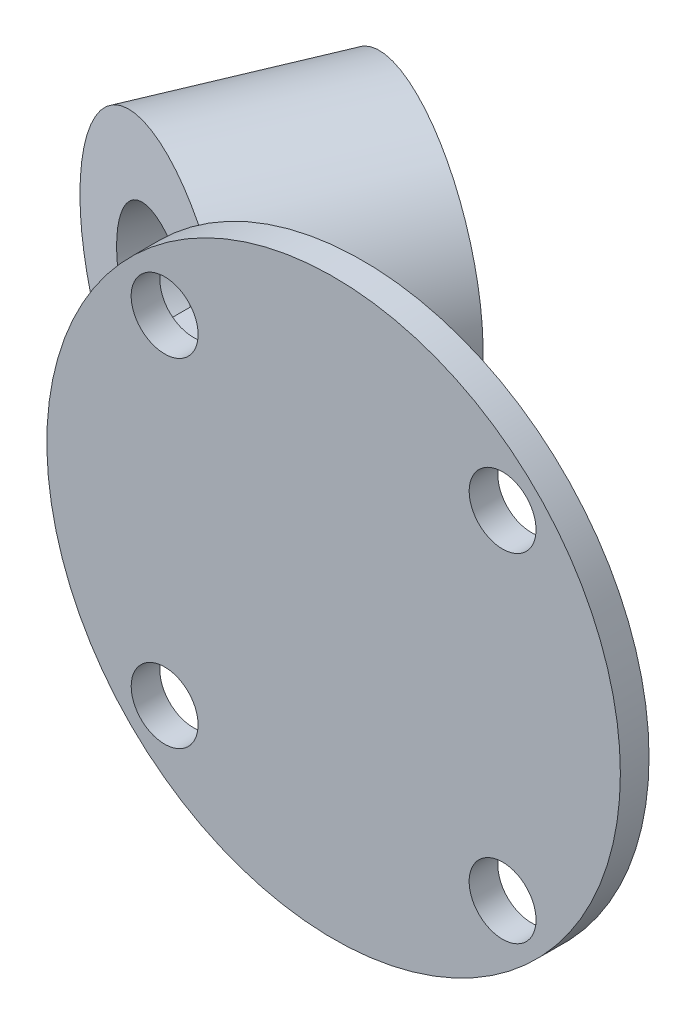
SolidWorks part; units mm, degrees
ref_plane "前视基准面" through (0, 0, 0) normal (0, 0, 1) x (1, 0, 0)
ref_plane "上视基准面" through (0, 0, 0) normal (0, 1, 0) x (1, 0, 0)
ref_plane "右视基准面" through (0, 0, 0) normal (1, 0, 0) x (0, 0, -1)
sketch "草图2" plane through (0, 0, 0) normal (0, 0, 1) x (1, 0, 0)
  circle A0 centre (0, 0) radius 30
  dimension "D1" = 60
extrude "凸台-拉伸1" add sketch "草图2" along normal blind 3 contours A0
sketch "草图3" plane through (0, 0, 3) normal (0, 0, 1) x (1, 0, 0)
  line L2 (0, -1.65) -> (0, 1.65) construction
  line L3 (1.65, 0) -> (-1.65, 0) construction
  circle A0 centre (-17.6777, 17.6777) radius 3.5
  circle A4 centre (17.6777, 17.6777) radius 3.5
  circle A5 centre (17.6777, -17.6777) radius 3.5
  circle A6 centre (-17.6777, -17.6777) radius 3.5
  dimension "D1" = 25
  dimension "D2" = 7
  dimension "D3" = 35.3553
  dimension "D4" = 35.3553
extrude "切除-拉伸1" cut sketch "草图3" against normal blind 3
sketch "草图4" plane through (0, 0, 0) normal (1, 0, 0) x (0, 0, -1)
  line L0 (-3, 30) -> (-3, -30) construction
  line L1 (0, -5) -> (-3, -5)
  line L2 (0, -5) -> (0, 5)
  line L3 (0, 5) -> (-3, 5)
  line L4 (-3, -5) -> (-3, 5)
  line L5 (0, -5) -> (-3, 5) construction
  line L6 (0, 5) -> (-3, -5) construction
  point P0 (-1.5, 0)
  dimension "D1" = 10
  dimension "D2" = 3
sketch "草图13" plane through (0, 0, 0) normal (0, 1, 0) x (1, 0, 0)
  line L0 (-35, 20) -> (0, 102.9156)
  line L1 (0, -58.2536) -> (0, 58.2536) construction
  line L2 (-35, 20) -> (0, 5.2259)
  line L3 (-47.85, 0) -> (47.85, 0) construction
  dimension "D1" = 35
  dimension "D2" = 90
  dimension "D3" = 0
  dimension "D4" = 20
  dimension "D5" = 90
  dimension "D6" = 0
  dimension "D7" = 82.9156
  dimension "D8" = 67.115
ref_plane "基准面2" through (1.8723, 0, -4.4356) normal (-0.3889, 0, 0.9213) x (0.9213, 0, 0.3889)
sketch "草图15" plane through (1.8723, 0, -4.4356) normal (-0.3889, 0, 0.9213) x (0.9213, 0, 0.3889)
  circle A0 centre (-40.0227, 0) radius 7.8
  circle A1 centre (-40.0227, 0) radius 15
  dimension "D1" = 15.6
  dimension "D2" = 30
ref_plane "基准面3" through (-0.0721, 0, 0.1708) normal (-0.3889, 0, 0.9213) x (0.9213, 0, 0.3889)
sketch "草图24" plane through (-0.0721, 0, 0.1708) normal (-0.3889, 0, 0.9213) x (0.9213, 0, 0.3889)
  circle A0 centre (-40.0227, 0) radius 15
  circle A1 centre (-40.0227, 0) radius 7.8
sketch "草图25" plane through (0, 0, 0) normal (0, 1, 0) x (1, 0, 0)
  line L0 (-29.7584, 12.3602) -> (-23.1252, 9.5602)
  line L1 (-50.7637, 21.2269) -> (-23.1252, 9.5602) construction
  line L2 (-44.1305, 18.4269) -> (-29.7584, 12.3602) construction
  line L3 (-13.8658, 5.6517) -> (13.7216, -5.9934) construction
  line L4 (-23.1252, 9.5602) -> (-15.3474, 27.9859)
  line L5 (-15.3474, 27.9859) -> (-21.478, 30.5738)
  line L6 (-21.478, 30.5738) -> (-29.7584, 12.3602)
  line L7 (-35, 20) -> (-36.9444, 15.3936)
  line L8 (-42.186, 23.0333) -> (-27.814, 16.9667) construction
  dimension "D1" = 20
  dimension "D2" = 6.6544
revolve "旋转2" add sketch "草图25" angle 360 about L7
sketch "草图26" plane through (0, 0, 0) normal (0, 1, 0) x (1, 0, 0)
  line L0 (-29.7584, 12.3602) -> (-29.7584, 0)
  line L1 (30, 0) -> (-30, 0) construction
  line L2 (-29.7584, 0) -> (0, 0)
  line L3 (0, 0) -> (-21.1807, 14.1667)
  line L4 (-48.8193, 25.8333) -> (-21.1807, 14.1667) construction
  line L5 (-23.1252, 9.5602) -> (-15.3474, 27.9859) construction
  line L7 (-21.1807, 14.1667) -> (-26.7691, 16.5256)
  line L8 (-26.7691, 16.5256) -> (-29.7584, 12.3602)
extrude "凸台-拉伸2" add sketch "草图26" along normal mid plane 10
